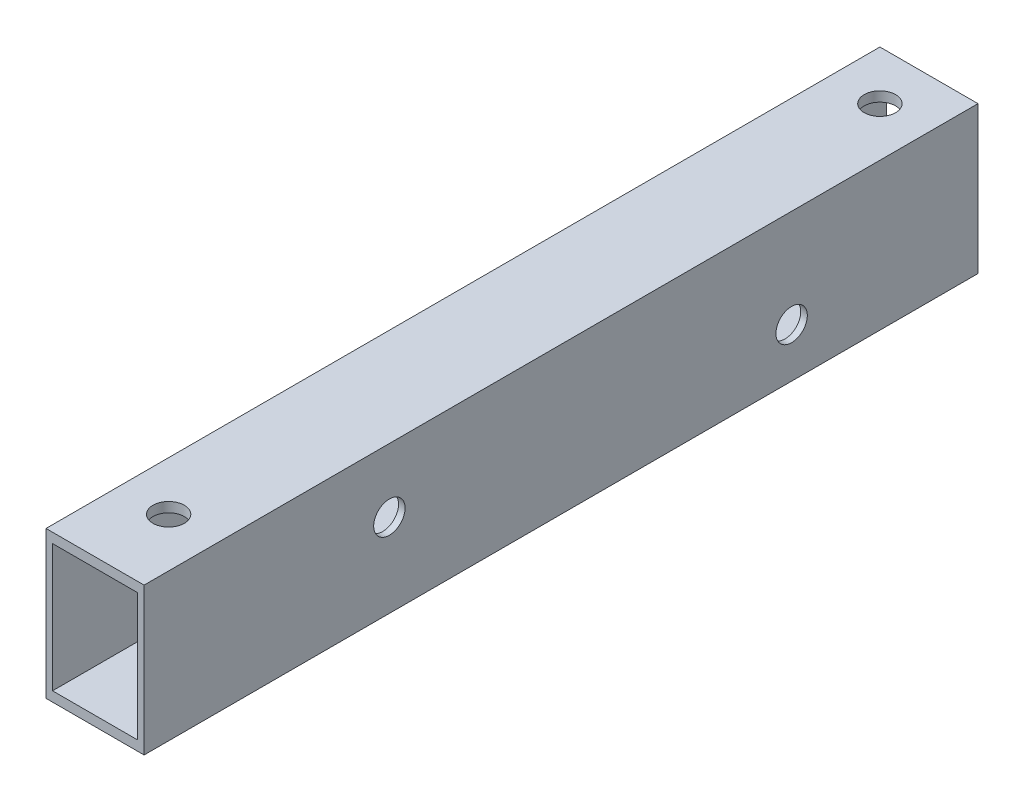
SolidWorks part; units mm, degrees
ref_plane "正面" through (0, 0, 0) normal (0, 0, 1) x (1, 0, 0)
ref_plane "平面" through (0, 0, 0) normal (0, 1, 0) x (1, 0, 0)
ref_plane "右側面" through (0, 0, 0) normal (1, 0, 0) x (0, 0, -1)
sketch "ｽｹｯﾁ1" plane through (0, 0, 0) normal (0, 0, 1) x (1, 0, 0)
  line L1 (-5, -7.5) -> (5, -7.5)
  line L2 (-5, -7.5) -> (-5, 7.5)
  line L3 (-5, 7.5) -> (5, 7.5)
  line L4 (5, -7.5) -> (5, 7.5)
  line L5 (-5, -7.5) -> (5, 7.5) construction
  line L6 (-5, 7.5) -> (5, -7.5) construction
  line L7 (-4.3333, -6.5) -> (4.3333, -6.5)
  line L8 (-4.3333, -6.5) -> (-4.3333, 6.5)
  line L9 (-4.3333, 6.5) -> (4.3333, 6.5)
  line L10 (4.3333, -6.5) -> (4.3333, 6.5)
  line L11 (-4.3333, -6.5) -> (4.3333, 6.5) construction
  line L12 (-4.3333, 6.5) -> (4.3333, -6.5) construction
  point P0 (0, 0)
  point P6 (0, 0)
  dimension "D1" = 1
  dimension "D2" = 10
  dimension "D3" = 15
extrude "ﾎﾞｽ - 押し出し1" add sketch "ｽｹｯﾁ1" along normal blind 85
sketch "ｽｹｯﾁ3" plane through (0, 7.5, 0) normal (0, 1, 0) x (1, 0, 0)
  line L0 (5, -85) -> (-5, -85) construction
  line L1 (-5, -85) -> (-5, 0) construction
  line L2 (5, 0) -> (-5, 0) construction
  line L3 (-5, -85) -> (-5, 0) construction
  circle A0 centre (0, -77.5) radius 1.6
  circle A1 centre (0, -5) radius 1.6
  dimension "D1" = 3.2
  dimension "D2" = 7.5
  dimension "D3" = 5
  dimension "D4" = 3.2
  dimension "D5" = 5
  dimension "D6" = 5
extrude "ｶｯﾄ - 押し出し2" cut sketch "ｽｹｯﾁ3" against normal through all
sketch "ｽｹｯﾁ4" plane through (-5, 0, 0) normal (-1, 0, 0) x (0, 0, 1)
  line L0 (85, 7.5) -> (85, -7.5) construction
  line L1 (85, 7.5) -> (0, 7.5) construction
  line L2 (85, -7.5) -> (0, -7.5) construction
  line L3 (0, -7.5) -> (0, 7.5) construction
  circle A0 centre (60, 1) radius 1.6
  circle A1 centre (19, -2.5) radius 1.6
  dimension "D1" = 3.2
  dimension "D2" = 25
  dimension "D4" = 5
  dimension "D5" = 3.2
  dimension "D6" = 19
  dimension "D3" = 6.5
extrude "ｶｯﾄ - 押し出し3" cut sketch "ｽｹｯﾁ4" against normal through all
